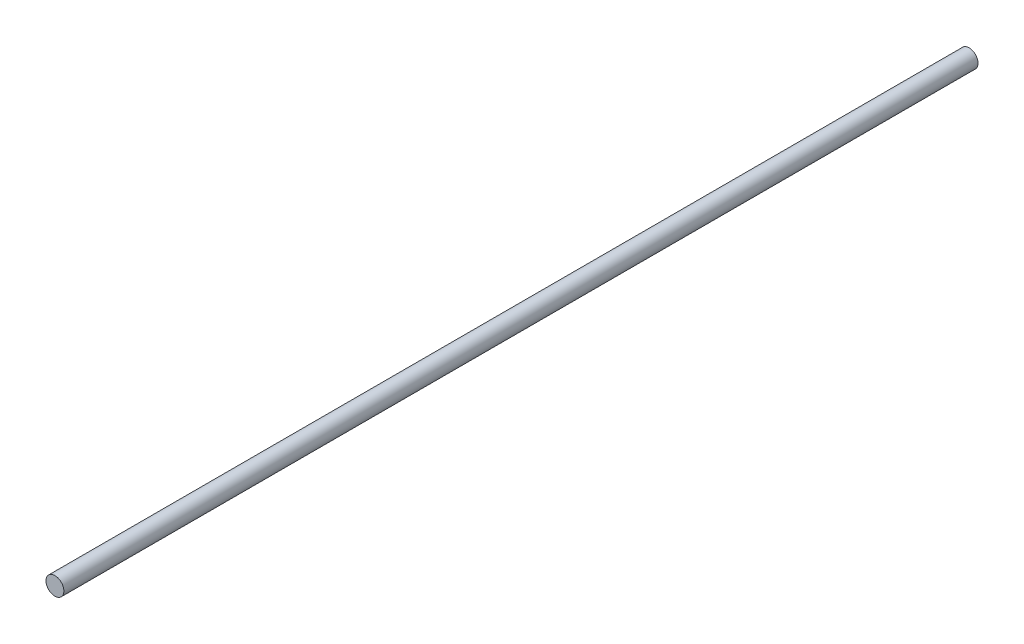
SolidWorks part; units mm, degrees
ref_plane "前视基准面" through (0, 0, 0) normal (0, 0, 1) x (1, 0, 0)
ref_plane "上视基准面" through (0, 0, 0) normal (0, 1, 0) x (1, 0, 0)
ref_plane "右视基准面" through (0, 0, 0) normal (1, 0, 0) x (0, 0, -1)
sketch "草图1" plane through (0, 0, 0) normal (0, 0, 1) x (1, 0, 0)
  circle A0 centre (0, 0) radius 3
extrude "凸台-拉伸1" add sketch "草图1" along normal blind 307
